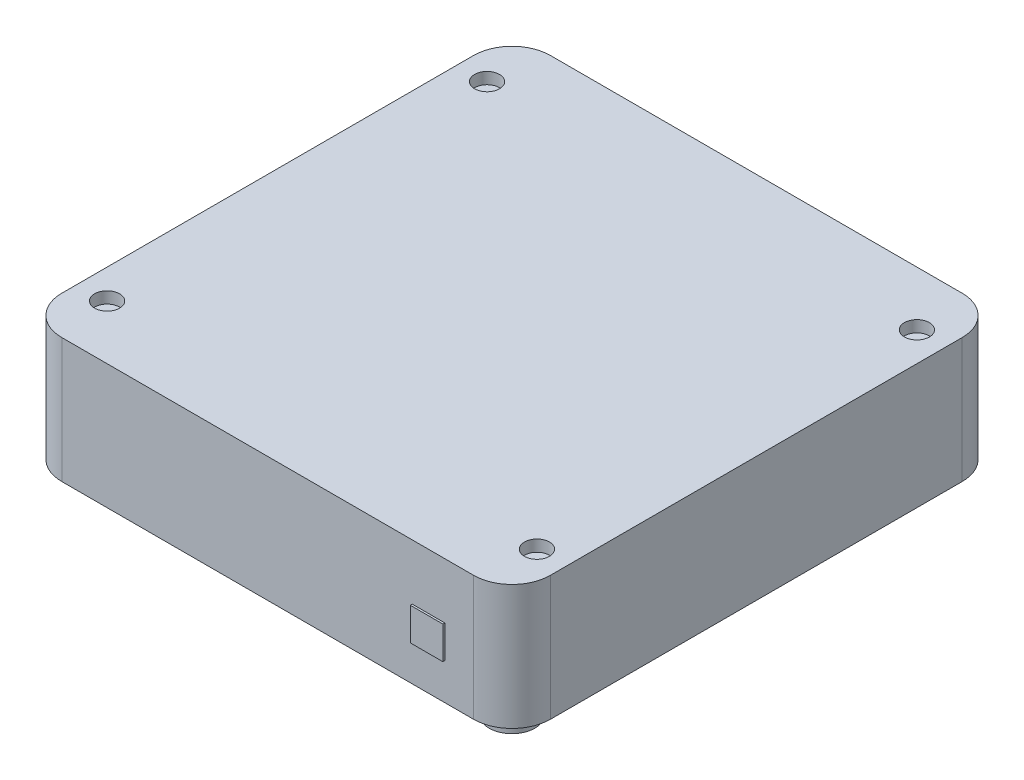
SolidWorks part; units mm, degrees
material "1023 碳钢板 (SS)"
ref_plane "前视基准面" through (0, 0, 0) normal (0, 0, 1) x (1, 0, 0)
ref_plane "上视基准面" through (0, 0, 0) normal (0, 1, 0) x (1, 0, 0)
ref_plane "右视基准面" through (0, 0, 0) normal (1, 0, 0) x (0, 0, -1)
other "Configuration Table"
sketch "草图1" plane through (0, 0, 0) normal (0, 1, 0) x (1, 0, 0)
  line L1 (-63.65, 63.65) -> (63.65, 63.65)
  line L2 (-63.65, 63.65) -> (-63.65, -63.65)
  line L3 (-63.65, -63.65) -> (63.65, -63.65)
  line L4 (63.65, 63.65) -> (63.65, -63.65)
  line L5 (-63.65, 63.65) -> (63.65, -63.65) construction
  line L6 (-63.65, -63.65) -> (63.65, 63.65) construction
  point P0 (0, 0)
  dimension "D1" = 127.3
  dimension "D2" = 127.3
extrude "凸台-拉伸1" add sketch "草图1" along normal mid plane 32.5
sketch "草图2" plane through (0, 0, 63.65) normal (0, 0, 1) x (1, 0, 0)
  line L0 (63.65, 16.25) -> (63.65, -16.25) construction
  line L1 (37.65, 1.75) -> (46.15, 1.75)
  line L2 (37.65, 1.75) -> (37.65, -6.75)
  line L3 (37.65, -6.75) -> (46.15, -6.75)
  line L4 (46.15, 1.75) -> (46.15, -6.75)
  line L5 (-63.65, -16.25) -> (63.65, -16.25) construction
  dimension "D1" = 8.5
  dimension "D2" = 8.5
  dimension "D3" = 17.5
  dimension "D4" = 9.5
extrude "凸台-拉伸2" add sketch "草图2" along normal mid plane 1
sketch "草图3" plane through (0, -16.25, 0) normal (0, -1, 0) x (1, 0, 0)
  line L0 (63.65, 63.65) -> (63.65, -63.65) construction
  line L1 (-63.65, 63.65) -> (63.65, 63.65) construction
  circle A0 centre (51.65, 51.65) radius 6
  dimension "D1" = 12
  dimension "D2" = 12
  dimension "D3" = 12
extrude "凸台-拉伸3" add sketch "草图3" along normal blind 6
mirror "镜向1" about plane through (0, 0, 0) normal (0, 0, 1) of "凸台-拉伸3"
mirror "镜向2" about plane through (0, 0, 0) normal (1, 0, 0) of "镜向1", "凸台-拉伸3"
sketch "草图4" plane through (0, 16.25, 0) normal (0, 1, 0) x (1, 0, 0)
  line L2 (0, 0) -> (0, 63.65) construction
  line L3 (63.65, 63.65) -> (-63.65, 63.65) construction
  line L4 (0, 0) -> (63.65, 0) construction
  line L5 (63.65, -63.65) -> (63.65, 63.65) construction
  circle A0 centre (56, 49.5) radius 3.25
  dimension "D1" = 6.5
  dimension "D2" = 112
  dimension "D3" = 99
extrude "切除-拉伸1" cut sketch "草图4" against normal blind 3
mirror "镜向3" about plane through (0, 0, 0) normal (1, 0, 0) of "切除-拉伸1"
mirror "镜向4" about plane through (0, 0, 0) normal (0, 0, 1) of "镜向3", "切除-拉伸1"
fillet "圆角1" radius 10 4 edges at (-63.65, 0, 63.65) (-63.65, 0, -63.65) (63.65, 0, -63.65) (63.65, 0, 63.65)
sketch "草图5" plane through (0, -16.25, 0) normal (0, -1, 0) x (1, 0, 0)
  line L0 (-48, 0) -> (48, 0) construction
  circle A0 centre (-48, 0) radius 1.6
  circle A1 centre (48, 0) radius 1.6
  point P4 (0, 0)
  dimension "D2" = 3.2
  dimension "D1" = 96
extrude "切除-拉伸2" cut sketch "草图5" against normal blind 3
